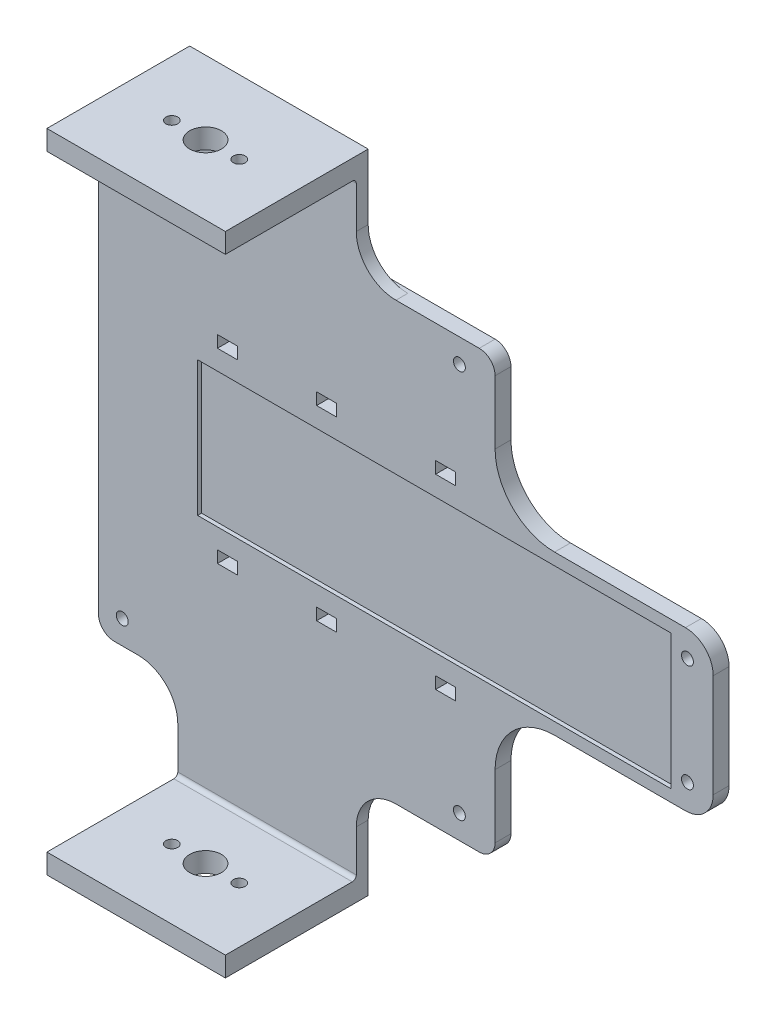
SolidWorks part; units mm, degrees
ref_plane "Front Plane" through (0, 0, 0) normal (0, 0, 1) x (1, 0, 0)
ref_plane "Top Plane" through (0, 0, 0) normal (0, 1, 0) x (1, 0, 0)
ref_plane "Right Plane" through (0, 0, 0) normal (1, 0, 0) x (0, 0, -1)
sketch "Sketch1" plane through (0, 0, 0) normal (0, 0, 1) x (1, 0, 0)
  line L1 (77.5, 55) -> (-77.5, 55)
  line L2 (77.5, 55) -> (77.5, -55)
  line L3 (77.5, -55) -> (-77.5, -55)
  line L4 (-77.5, 55) -> (-77.5, -55)
  line L5 (77.5, 55) -> (-77.5, -55) construction
  line L6 (77.5, -55) -> (-77.5, 55) construction
  point P0 (0, 0)
  dimension "D1" = 155
  dimension "D2" = 110
extrude "Boss-Extrude1" add sketch "Sketch1" along normal blind 4
sketch "Sketch2" plane through (0, 0, 4) normal (0, 0, 1) x (1, 0, 0)
  line L0 (-77.5, 0) -> (77.5, 0) construction
  line L1 (-77.5, 55) -> (-77.5, -55) construction
  line L2 (77.5, -55) -> (77.5, 55) construction
  line L3 (77.5, -20) -> (77.5, -55)
  line L4 (22.5, 20) -> (77.5, 20)
  line L5 (22.5, 20) -> (22.5, 55)
  line L6 (77.5, 55) -> (-77.5, 55) construction
  line L7 (22.5, -20) -> (22.5, -55)
  line L8 (22.5, -20) -> (77.5, -20)
  line L9 (77.5, -55) -> (22.5, -55)
  line L10 (22.5, 55) -> (77.5, 55)
  line L11 (77.5, 55) -> (77.5, 20)
  line L12 (-77.5, -55) -> (77.5, -55) construction
  line L23 (-63, 0) -> (-63, -35) construction
  line L30 (-27.5, 55) -> (-27.5, -55) construction
  circle A9 centre (-71.5, 49) radius 1.5
  circle A10 centre (-71.5, -49) radius 1.5
  circle A14 centre (71, 13.5) radius 1.5
  circle A17 centre (71, -13.5) radius 1.5
  circle A18 centre (13.5, 49) radius 1.5
  circle A19 centre (13.5, -49) radius 1.5
  point P8 (22.5, 0)
  point P9 (-49.5, 0)
  point P10 (22.5, 20)
  point P50 (-77.5, 55)
  point P51 (-27.5, 55)
  dimension "D15" = 3
  dimension "D16" = 6
  dimension "D19" = 3
  dimension "D20" = 6.5
  dimension "D21" = 6.5
  dimension "D23" = 3
  dimension "D24" = 9
  dimension "D1" = 72
  dimension "D3" = 55
  dimension "D5" = 20
  dimension "D12" = 20
  dimension "D17" = 6
  dimension "D18" = 50
extrude "Cut-Extrude1" cut sketch "Sketch2" against normal blind 148
sketch3d "3DSketch1"
  point P0 (57.5415, 7.1901, 4)
ref_plane "Plane1" through (0, 0, 4) normal (0, 0, 1) x (1, 0, 0)
fillet "Fillet2" radius 15 2 edges at (22.5, 20, 2) (22.5, -20, 2)
fillet "Fillet3" radius 7 2 edges at (77.5, -20, 2) (77.5, 20, 2)
sketch "Sketch3" plane through (0, 0, 4) normal (0, 0, 1) x (1, 0, 0)
  line L0 (-12.5, 55) -> (-12.5, 81.5)
  line L1 (22.5, 55) -> (-77.5, 55) construction
  line L2 (-12.5, 81.5) -> (-57.5, 81.5)
  line L3 (-57.5, 81.5) -> (-57.5, 55)
  line L4 (77.5, -13) -> (77.5, 13) construction
  line L5 (-77.5, 55) -> (-77.5, -55) construction
  line L6 (-57.5, 55) -> (-12.5, 55)
  line L7 (-77.5, 0) -> (77.5, 0) construction
  line L8 (-57.5, -81.5) -> (-57.5, -55)
  line L9 (-12.5, -81.5) -> (-57.5, -81.5)
  line L10 (-12.5, -55) -> (-12.5, -81.5)
  line L11 (-57.5, -55) -> (-12.5, -55)
  point P16 (-23.9005, 23.5)
  point P17 (-23.9005, -23.5)
  dimension "D1" = 90
  dimension "D2" = 26.5
  dimension "D3" = 20
  dimension "D4" = 58
extrude "Boss-Extrude2" add sketch "Sketch3" against normal blind 3
sketch "Sketch5" plane through (0, 0, 4) normal (0, 0, 1) x (1, 0, 0)
  line L0 (-57.5, 76.5) -> (-12.5, 76.5)
  line L1 (-57.5, 81.5) -> (-57.5, 55) construction
  line L2 (-12.5, 55) -> (-12.5, 81.5) construction
  line L3 (-77.5, 0) -> (77.5, 0) construction
  line L4 (-77.5, 55) -> (-77.5, -55) construction
  line L5 (77.5, -13) -> (77.5, 13) construction
  line L6 (-12.5, 81.5) -> (-57.5, 81.5) construction
  line L7 (-57.5, -76.5) -> (-12.5, -76.5)
  line L8 (-57.5, 76.5) -> (-57.5, 81.5)
  line L9 (-57.5, 81.5) -> (-12.5, 81.5)
  line L10 (-12.5, 81.5) -> (-12.5, 76.5)
  line L11 (-12.5, -81.5) -> (-12.5, -76.5)
  line L12 (-57.5, -81.5) -> (-12.5, -81.5)
  line L13 (-57.5, -76.5) -> (-57.5, -81.5)
  dimension "D1" = 5
extrude "Boss-Extrude3" add sketch "Sketch5" along normal blind 33
sketch "Sketch6" plane through (0, 81.5, 0) normal (0, 1, 0) x (1, 0, 0)
  line L0 (-35, -1) -> (-35, -37) construction
  line L1 (-12.5, -1) -> (-57.5, -1) construction
  line L2 (-12.5, -37) -> (-57.5, -37) construction
  line L3 (-57.5, -1) -> (-12.5, -1) construction
  circle A0 centre (-35, -19.5) radius 4
  circle A1 centre (-43.5, -19.5) radius 1.5
  circle A2 centre (-26.5, -19.5) radius 1.5
  dimension "D1" = 8
  dimension "D2" = 3
  dimension "D3" = 18.5
  dimension "D4" = 18.5
extrude "Cut-Extrude2" cut sketch "Sketch6" against normal blind 223
fillet "Fillet4" radius 10 4 edges at (-57.5, -55, 2.5) (-12.5, -55, 2.5) (-57.5, 55, 2.5) (-12.5, 55, 2.5)
fillet "Fillet5" radius 1 2 edges at (-35, -76.5, 4) (-35, 76.5, 4)
ref_plane "Plane2" through (-77.5, -55, 4) normal (0, -1, 0) x (-1, 0, 0)
sketch "Sketch8" plane through (0, 0, 0) normal (0, 0, -1) x (-1, 0, 0)
  line L0 (77.5, 0) -> (-77.5, 0) construction
  line L1 (77.5, 55) -> (77.5, -55) construction
  line L2 (-77.5, -13) -> (-77.5, 13) construction
  line L3 (52.5, -17) -> (52.5, 17)
  line L4 (52.5, 17) -> (-66.8118, 17)
  line L5 (-66.8118, 17) -> (-66.8118, -17)
  line L6 (52.5, -17) -> (-66.8118, -17)
  point P11 (52.5, 0)
  point P12 (-66.8118, 0)
  dimension "D1" = 25
  dimension "D2" = 17
sketch "Sketch9" plane through (0, 0, 4) normal (0, 0, 1) x (1, 0, 0)
  line L0 (-52.5, -17) -> (66.8118, -17)
  line L1 (66.8118, -17) -> (66.8118, 17)
  line L2 (66.8118, 17) -> (-52.5, 17)
  line L3 (-52.5, 17) -> (-52.5, -17)
extrude "Cut-Extrude4" cut sketch "Sketch9" against normal blind 1
fillet "Fillet8" radius 4 4 edges at (22.5, -55, 2) (-77.5, -55, 2) (22.5, 55, 2) (-77.5, 55, 2)
sketch "Sketch10" plane through (0, 0, 4) normal (0, 0, 1) x (1, 0, 0)
  line L0 (-52.5, 17) -> (66.8118, 17) construction
  line L1 (-47.5, 25) -> (-42.5, 25)
  line L2 (-47.5, 25) -> (-47.5, 22)
  line L3 (-47.5, 22) -> (-42.5, 22)
  line L4 (-42.5, 25) -> (-42.5, 22)
  line L5 (22.5, 35) -> (22.5, 51) construction
  line L6 (-22.5, 25) -> (-17.5, 25)
  line L7 (-22.5, 25) -> (-22.5, 22)
  line L8 (-22.5, 22) -> (-17.5, 22)
  line L9 (-17.5, 25) -> (-17.5, 22)
  line L10 (7.5, 25) -> (12.5, 25)
  line L11 (7.5, 25) -> (7.5, 22)
  line L12 (7.5, 22) -> (12.5, 22)
  line L13 (12.5, 25) -> (12.5, 22)
  line L14 (-77.5, 0) -> (77.5, 0) construction
  line L15 (-77.5, 51) -> (-77.5, -51) construction
  line L16 (12.5, -25) -> (12.5, -22)
  line L17 (7.5, -22) -> (12.5, -22)
  line L18 (7.5, -25) -> (7.5, -22)
  line L19 (7.5, -25) -> (12.5, -25)
  line L20 (-17.5, -25) -> (-17.5, -22)
  line L21 (-22.5, -22) -> (-17.5, -22)
  line L22 (-22.5, -25) -> (-22.5, -22)
  line L23 (-22.5, -25) -> (-17.5, -25)
  line L24 (-42.5, -25) -> (-42.5, -22)
  line L25 (-47.5, -22) -> (-42.5, -22)
  line L26 (-47.5, -25) -> (-47.5, -22)
  line L27 (-47.5, -25) -> (-42.5, -25)
  point P18 (-17.5, 23.5)
  dimension "D1" = 3
  dimension "D2" = 5
  dimension "D3" = 5
  dimension "D4" = 75
  dimension "D5" = 5
  dimension "D6" = 3
  dimension "D7" = 5
  dimension "D8" = 0
  dimension "D9" = 20
  dimension "D10" = 3
  dimension "D11" = 5
  dimension "D12" = 0
  dimension "D13" = 25
extrude "Cut-Extrude5" cut sketch "Sketch10" against normal blind 4
